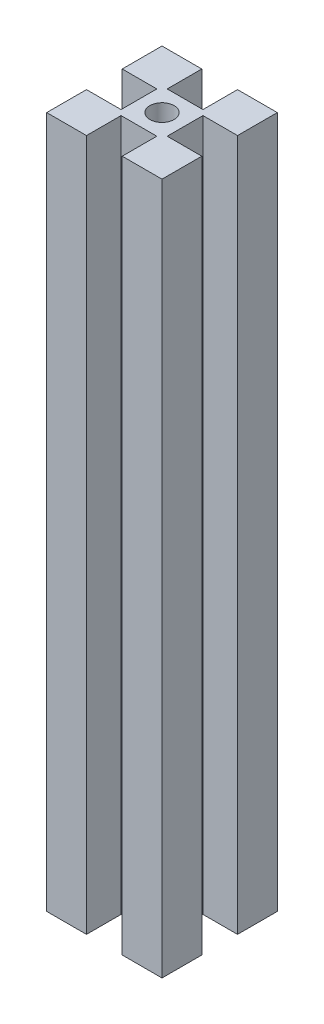
SolidWorks part; units mm, degrees
ref_plane "Front Plane" through (0, 0, 0) normal (0, 0, 1) x (1, 0, 0)
ref_plane "Top Plane" through (0, 0, 0) normal (0, 1, 0) x (1, 0, 0)
ref_plane "Right Plane" through (0, 0, 0) normal (1, 0, 0) x (0, 0, -1)
sketch "SK_Profile" plane through (0, 0, 0) normal (0, 1, 0) x (1, 0, 0)
  line L0 (10, -10) -> (10, -3.1)
  line L1 (10, -3.1) -> (4, -3.1)
  line L2 (4, -3.1) -> (4, 3.1)
  line L3 (4, 3.1) -> (10, 3.1)
  line L4 (10, 3.1) -> (10, 10)
  line L5 (10, 10) -> (3.1, 10)
  line L6 (3.1, 10) -> (3.1, 4)
  line L7 (3.1, 4) -> (-3.1, 4)
  line L8 (-3.1, 4) -> (-3.1, 10)
  line L9 (-3.1, 10) -> (-10, 10)
  line L10 (-10, 10) -> (-10, 3.1)
  line L11 (-10, 3.1) -> (-4, 3.1)
  line L12 (-4, 3.1) -> (-4, -3.1)
  line L13 (-4, -3.1) -> (-10, -3.1)
  line L14 (-10, -3.1) -> (-10, -10)
  line L15 (-10, -10) -> (-3.1, -10)
  line L16 (-3.1, -10) -> (-3.1, -4)
  line L17 (-3.1, -4) -> (3.1, -4)
  line L18 (3.1, -4) -> (3.1, -10)
  line L19 (3.1, -10) -> (10, -10)
  circle A0 centre (0, 0) radius 2.1
extrude "Extrusion" add sketch "SK_Profile" along normal blind 120
